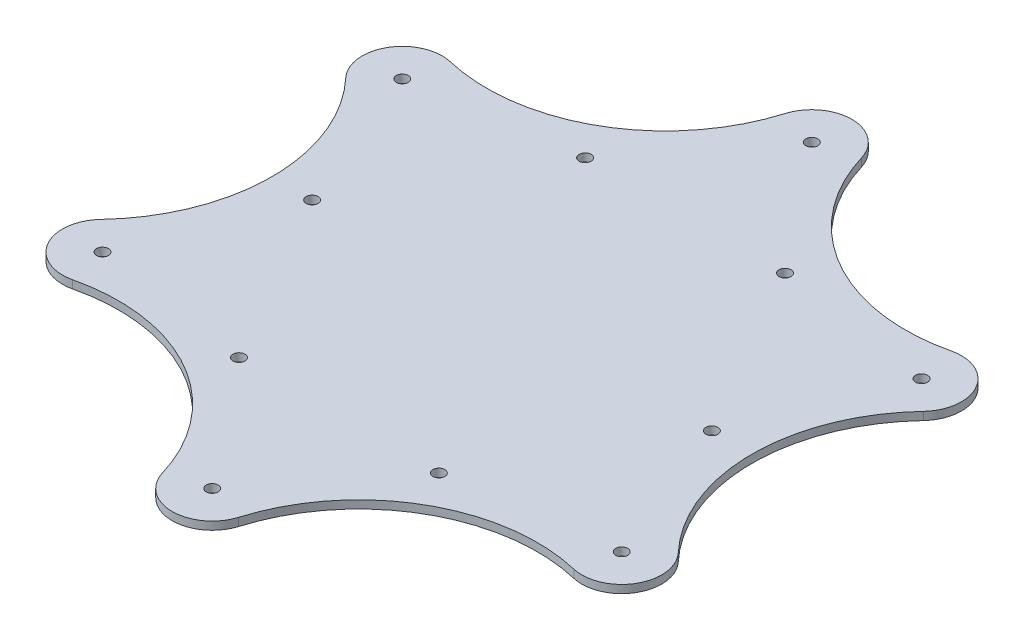
SolidWorks part; units mm, degrees
ref_plane "Front Plane" through (0, 0, 0) normal (0, 0, 1) x (1, 0, 0)
ref_plane "Top Plane" through (0, 0, 0) normal (0, 1, 0) x (1, 0, 0)
ref_plane "Right Plane" through (0, 0, 0) normal (1, 0, 0) x (0, 0, -1)
sketch "Sketch1" plane through (0, 0, 0) normal (0, 1, 0) x (1, 0, 0)
  arc A0 (9.565, 77.9173) -> (-9.5552, 77.9492) centre (0, 75) ccw
  arc A1 (-9.5552, 77.9492) -> (-62.6959, 47.2422) centre (-52.3729, 90.713) cw
  arc A2 (-62.6959, 47.2422) -> (-72.2836, 30.6995) centre (-64.9519, 37.5) ccw
  arc A3 (-72.2836, 30.6995) -> (-72.2609, -30.6751) centre (-104.7462, 0.0002) cw
  arc A4 (-72.2609, -30.6751) -> (-62.7283, -47.2497) centre (-64.9519, -37.5) ccw
  arc A5 (-62.7283, -47.2497) -> (-9.565, -77.9173) centre (-52.3733, -90.7128) cw
  arc A6 (-9.565, -77.9173) -> (9.5552, -77.9492) centre (0, -75) ccw
  arc A7 (9.5552, -77.9492) -> (62.6959, -47.2422) centre (52.3729, -90.713) cw
  arc A8 (62.6959, -47.2422) -> (72.2836, -30.6995) centre (64.9519, -37.5) ccw
  arc A9 (72.2836, -30.6995) -> (72.2609, 30.6751) centre (104.7462, -0.0002) cw
  arc A10 (72.2609, 30.6751) -> (62.7283, 47.2497) centre (64.9519, 37.5) ccw
  arc A11 (62.7283, 47.2497) -> (9.565, 77.9173) centre (52.3733, 90.7128) cw
  circle A12 centre (-64.9519, -37.5) radius 1.5
  circle A13 centre (0, 75) radius 1.5
  circle A14 centre (-25, 43.3013) radius 1.5
  circle A15 centre (-64.9519, 37.5) radius 1.5
  circle A16 centre (64.9519, 37.5) radius 1.5
  circle A17 centre (64.9519, -37.5) radius 1.5
  circle A18 centre (25, 43.3013) radius 1.5
  circle A19 centre (0, -75) radius 1.5
  circle A20 centre (-50, 0) radius 1.5
  circle A21 centre (25, -43.3013) radius 1.5
  circle A22 centre (-25, -43.3013) radius 1.5
  circle A23 centre (50, 0) radius 1.5
extrude "Boss-Extrude1" add sketch "Sketch1" along normal blind 2
